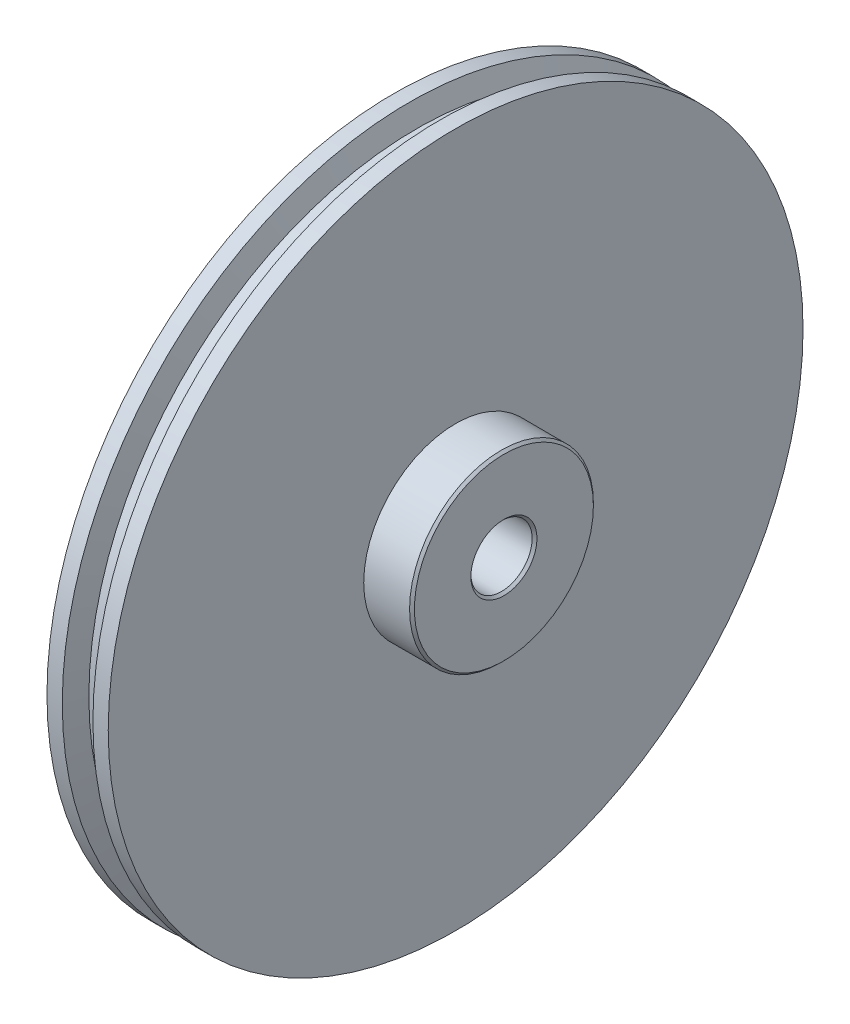
SolidWorks part; units mm, degrees
material "Polybutadiene (PB)"
ref_plane "Front Plane" through (0, 0, 0) normal (0, 0, 1) x (1, 0, 0)
ref_plane "Top Plane" through (0, 0, 0) normal (0, 1, 0) x (1, 0, 0)
ref_plane "Right Plane" through (0, 0, 0) normal (1, 0, 0) x (0, 0, -1)
sketch "Sketch2" plane through (0, 0, 0) normal (0, 0, 1) x (1, 0, 0)
  line L0 (0, 0) -> (59.7537, 0) construction
  line L1 (0, 0) -> (0, 50.4348) construction
  line L2 (-3.175, 3.175) -> (3.175, 3.175)
  line L3 (3.175, 3.175) -> (3.175, 36)
  line L4 (-3.175, 3.175) -> (-3.175, 36)
  line L5 (-3.175, 36) -> (-1.5875, 36)
  line L6 (-1.5875, 36) -> (-0.8336, 34)
  line L7 (-0.8336, 34) -> (0.8336, 34)
  line L8 (0.8336, 34) -> (1.5875, 36)
  line L9 (1.5875, 36) -> (3.175, 36)
  dimension "D1" = 3.175
  dimension "D2" = 36
  dimension "D3" = 6.35
  dimension "D4" = 2
  dimension "D6" = 3.175
revolve "Revolve1" add sketch "Sketch2" angle 360 about L0
sketch "Sketch3" plane through (3.175, 0, 0) normal (1, 0, 0) x (0, 0, -1)
  circle A0 centre (0, 0) radius 9.525
  dimension "D1" = 19.05
extrude "Boss-Extrude1" add sketch "Sketch3" along normal blind 5
sketch "Sketch4" plane through (8.175, 0, 0) normal (1, 0, 0) x (0, 0, -1)
  circle A0 centre (0, 0) radius 3.175
  dimension "D1" = 6.35
extrude "Cut-Extrude1" cut sketch "Sketch4" against normal through all
chamfer "Chamfer1" distance 0.25 angle 45 3 edges at (-3.175, 0, 3.175) (8.175, 0, -3.175) (8.175, 0, -9.525)
